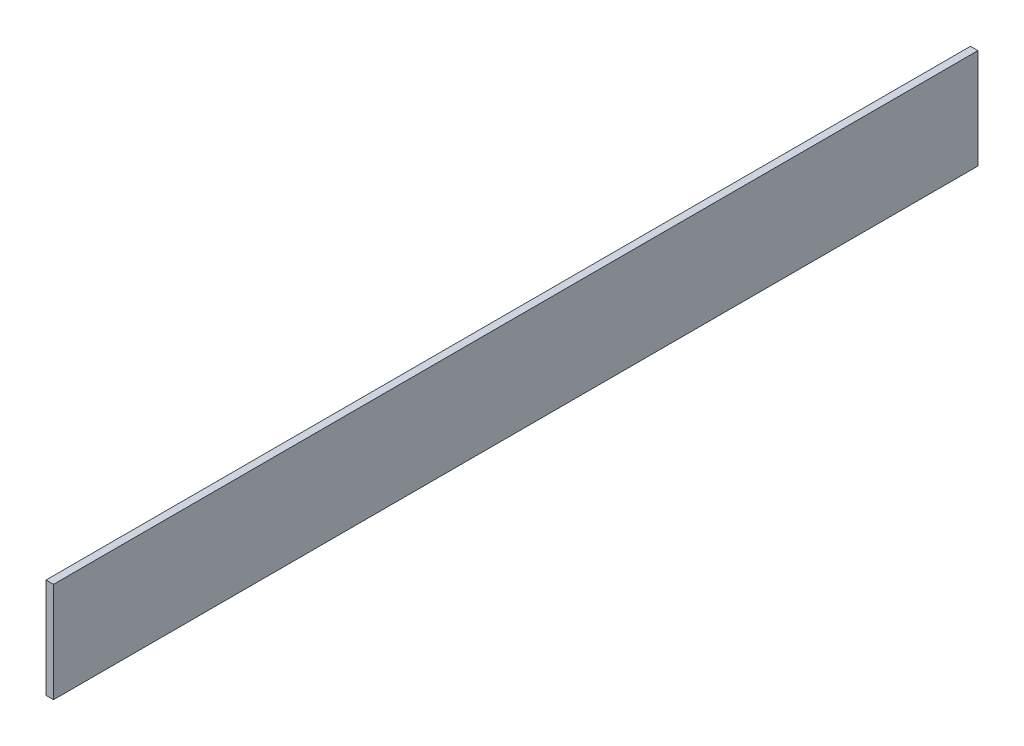
SolidWorks part; units mm, degrees
ref_plane "Front Plane" through (0, 0, 0) normal (0, 0, 1) x (1, 0, 0)
ref_plane "Top Plane" through (0, 0, 0) normal (0, 1, 0) x (1, 0, 0)
ref_plane "Right Plane" through (0, 0, 0) normal (1, 0, 0) x (0, 0, -1)
sketch "Sketch1" plane through (0, 0, 0) normal (1, 0, 0) x (0, 0, -1)
  line L1 (0, 0) -> (587.375, 0)
  line L2 (0, 0) -> (0, 63.5)
  line L3 (0, 63.5) -> (587.375, 63.5)
  line L4 (587.375, 0) -> (587.375, 63.5)
  dimension "D1" = 587.375
  dimension "D2" = 63.5
extrude "Boss-Extrude1" add sketch "Sketch1" along normal blind 4.7625
